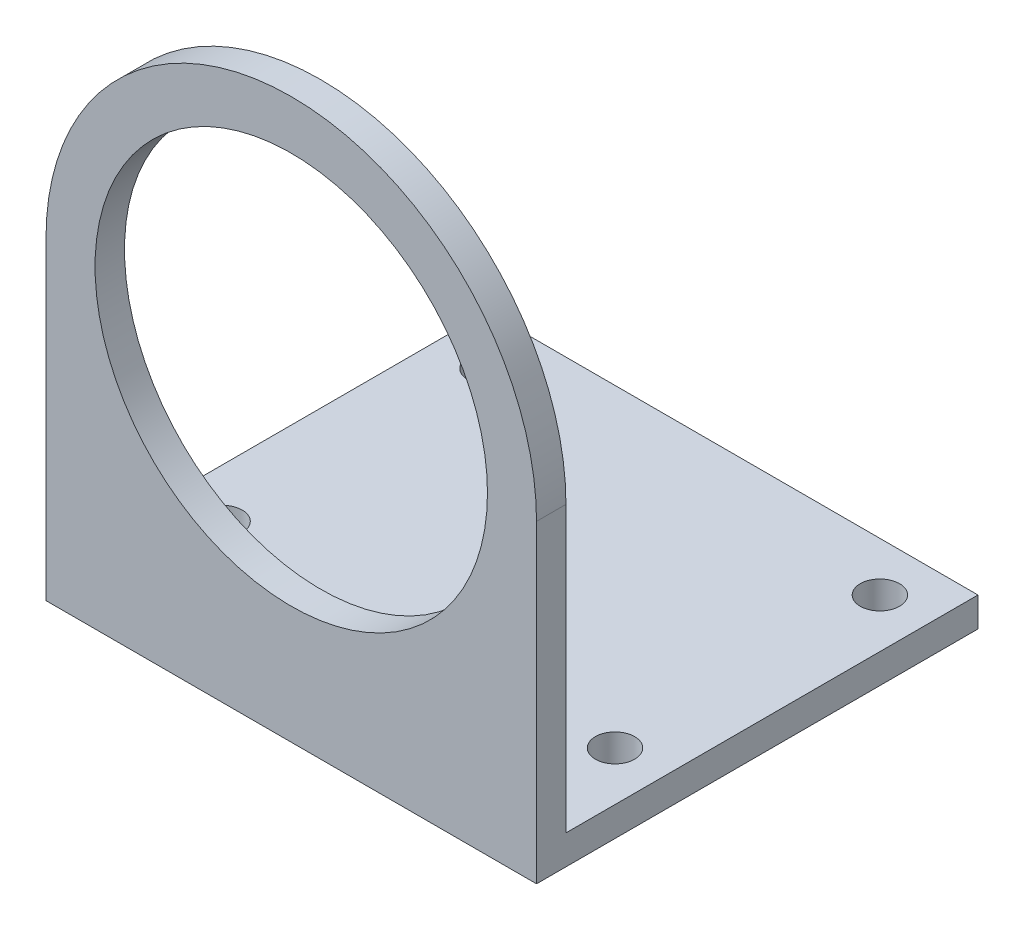
SolidWorks part; units mm, degrees
ref_plane "Front Plane" through (0, 0, 0) normal (0, 0, 1) x (1, 0, 0)
ref_plane "Top Plane" through (0, 0, 0) normal (0, 1, 0) x (1, 0, 0)
ref_plane "Right Plane" through (0, 0, 0) normal (1, 0, 0) x (0, 0, -1)
sketch "Sketch1" plane through (0, 0, 0) normal (0, 0, 1) x (1, 0, 0)
  line L0 (-25, 0) -> (25, 0)
  line L1 (-25, 0) -> (-25, 29)
  line L3 (25, 29) -> (25, 0)
  arc A0 (-25, 29) -> (25, 29) centre (0, 29) cw
  circle A1 centre (0, 29) radius 20
  point P4 (0, 0)
  dimension "D3" = 40
  dimension "D1" = 50
  dimension "D2" = 29
extrude "Boss-Extrude1" add sketch "Sketch1" along normal blind 3
sketch "Sketch2" plane through (0, 0, 3) normal (0, 0, 1) x (1, 0, 0)
  line L0 (-25, 0) -> (-25, -3)
  line L1 (-25, -3) -> (25, -3)
  line L2 (25, -3) -> (25, 0)
  line L3 (25, 0) -> (-25, 0)
  dimension "D1" = 3
  dimension "D2" = 50
extrude "Boss-Extrude2" add sketch "Sketch2" against normal blind 45
sketch "Sketch3" plane through (0, 0, 0) normal (0, 1, 0) x (1, 0, 0)
  line L0 (25, 42) -> (-25, 42) construction
  line L1 (25, 0) -> (-25, 0) construction
  line L2 (-25, 42) -> (-25, 0) construction
  line L3 (0, 0) -> (0, 19.9618) construction
  circle A0 centre (-20, 37) radius 2
  circle A1 centre (-20, 10) radius 2
  circle A2 centre (20, 10) radius 2
  circle A3 centre (20, 37) radius 2
  dimension "D1" = 4
  dimension "4" = 4
  dimension "D2" = 5
  dimension "D3" = 10
  dimension "D4" = 5
  dimension "D5" = 5
extrude "Cut-Extrude1" cut sketch "Sketch3" against normal through all
